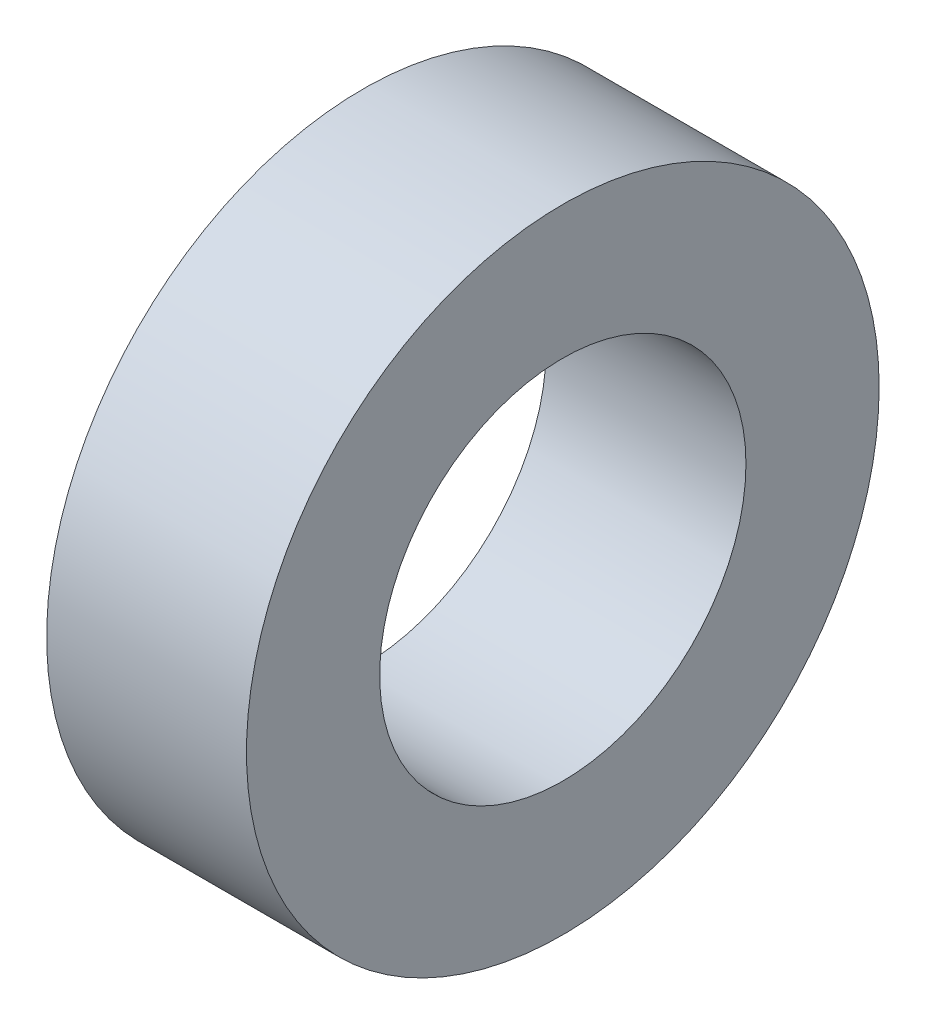
SolidWorks part; units mm, degrees
ref_plane "Alzado" through (0, 0, 0) normal (0, 0, 1) x (1, 0, 0)
ref_plane "Planta" through (0, 0, 0) normal (0, 1, 0) x (1, 0, 0)
ref_plane "Vista lateral" through (0, 0, 0) normal (1, 0, 0) x (0, 0, -1)
sketch "Croquis1" plane through (0, 0, 0) normal (1, 0, 0) x (0, 0, -1)
  circle A0 centre (0, 0) radius 2.75
  circle A1 centre (0, 0) radius 4.75
  dimension "D1" = 5.5
  dimension "D2" = 2
extrude "Saliente-Extruir1" add sketch "Croquis1" along normal blind 3
